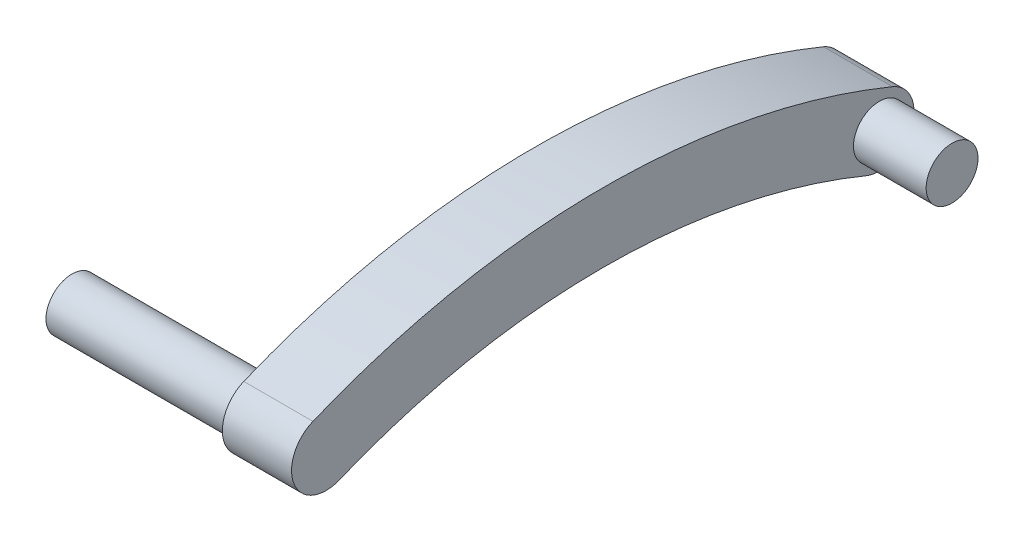
SolidWorks part; units mm, degrees
ref_plane "Front Plane" through (0, 0, 0) normal (0, 0, 1) x (1, 0, 0)
ref_plane "Top Plane" through (0, 0, 0) normal (0, 1, 0) x (1, 0, 0)
ref_plane "Right Plane" through (0, 0, 0) normal (1, 0, 0) x (0, 0, -1)
sketch "Sketch1" plane through (0, 0, 0) normal (1, 0, 0) x (0, 0, -1)
  line L0 (0, 0) -> (32, 0) construction
  arc A0 (-0.7619, 1.8492) -> (0.7619, -1.8492) centre (0, 0) ccw
  arc A1 (31.2381, -1.8492) -> (32.7619, 1.8492) centre (32, 0) ccw
  circle A2 centre (32, 0) radius 1.625 construction
  circle A3 centre (0, 0) radius 1.625 construction
  arc A4 (-0.7619, 1.8492) -> (32.7619, 1.8492) centre (16, -38.833) cw
  arc A5 (0.7619, -1.8492) -> (31.2381, -1.8492) centre (16, -38.833) cw
  dimension "D2" = 4
  dimension "D3" = 3.25
  dimension "D4" = 40
  dimension "D1" = 32
extrude "Boss-Extrude1" add sketch "Sketch1" along normal blind 4
sketch "Sketch2" plane through (4, 0, 0) normal (1, 0, 0) x (0, 0, -1)
  circle A0 centre (32, 0) radius 1.5
  dimension "D1" = 3
extrude "Boss-Extrude2" add sketch "Sketch2" along normal blind 4.2
sketch "Sketch3" plane through (0, 0, 0) normal (-1, 0, 0) x (0, 0, 1)
  circle A0 centre (0, 0) radius 1.5
  dimension "D1" = 3
extrude "Boss-Extrude3" add sketch "Sketch3" along normal blind 10.7
